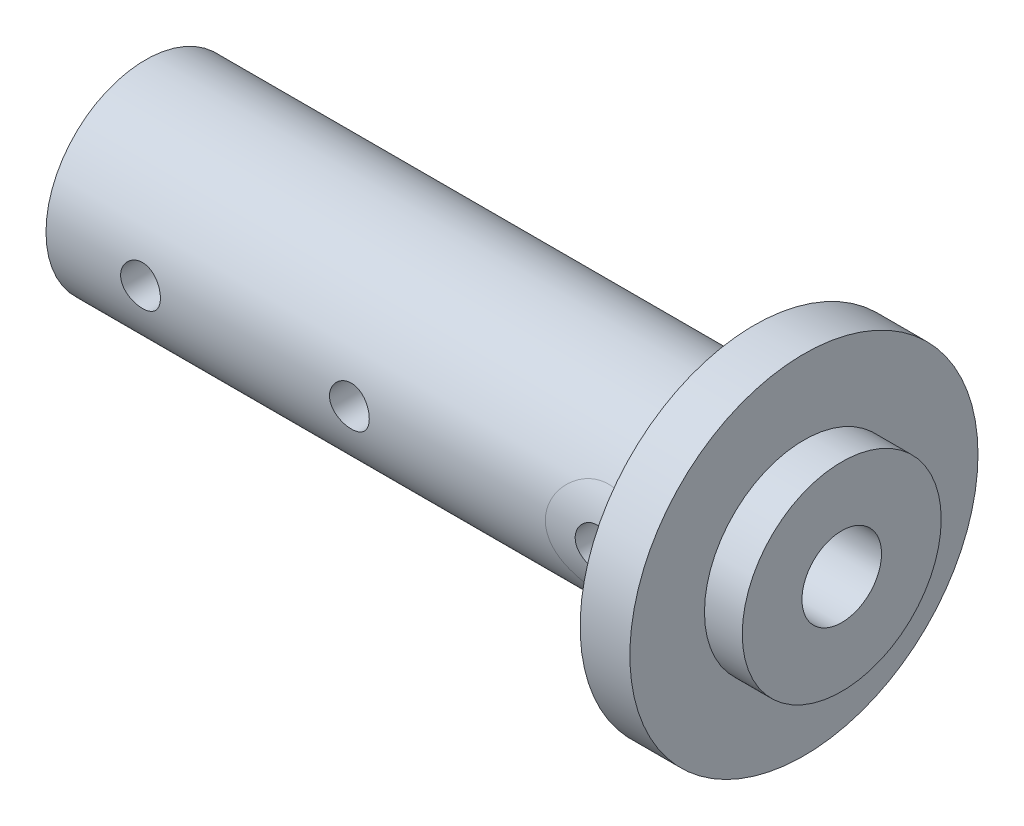
SolidWorks part; units mm, degrees
material "1.0117 (S235J2G4)"
ref_plane "Front Plane" through (0, 0, 0) normal (0, 0, 1) x (1, 0, 0)
ref_plane "Top Plane" through (0, 0, 0) normal (0, 1, 0) x (1, 0, 0)
ref_plane "Right Plane" through (0, 0, 0) normal (1, 0, 0) x (0, 0, -1)
sketch "Sketch1" plane through (0, 0, 0) normal (0, 1, 0) x (1, 0, 0)
  line L1 (-3.8, 17.5) -> (-8.8, 17.5)
  line L2 (-8.8, 17.5) -> (-8.8, 10)
  line L3 (-8.8, 10) -> (-70, 10)
  line L4 (-70, 10) -> (-70, 0)
  line L5 (-70, 0) -> (0, 0) construction
  line L6 (0, 0) -> (-70, 0)
  line L7 (-3.8, 17.5) -> (-3.8, 10)
  line L8 (-3.8, 10) -> (0, 10)
  line L9 (0, 10) -> (0, 4)
  line L10 (0, 4) -> (-70, 4)
  line L11 (-70, 4) -> (-70, 0)
  dimension "D1" = 5
  dimension "D2" = 17.5
  dimension "D3" = 10
  dimension "D4" = 70
  dimension "D5" = 3.8
  dimension "D6" = 4
  dimension "D7" = 70
revolve "Revolve2" add sketch "Sketch1" angle 360 about L6
sketch "Sketch5" plane through (0, 0, 0) normal (0, 0, 1) x (1, 0, 0)
  line L0 (-8.8, 17.5) -> (-8.8, -17.5) construction
  circle A0 centre (-39.5, 0) radius 2
  circle A1 centre (-60.5, 0) radius 2
  circle A2 centre (-39.5, 0) radius 2 construction
  circle A3 centre (-60.5, 0) radius 2 construction
  circle A4 centre (-14.8, 0) radius 2
  dimension "D1" = 6
extrude "Cut-Extrude2" cut sketch "Sketch5" against normal through all both and the other way through all
sketch "Sketch6" plane through (0, 0, 0) normal (0, 0, 1) x (1, 0, 0)
  circle A0 centre (-14.8, 0) radius 5
  dimension "D1" = 10
split line "Split Line1"
